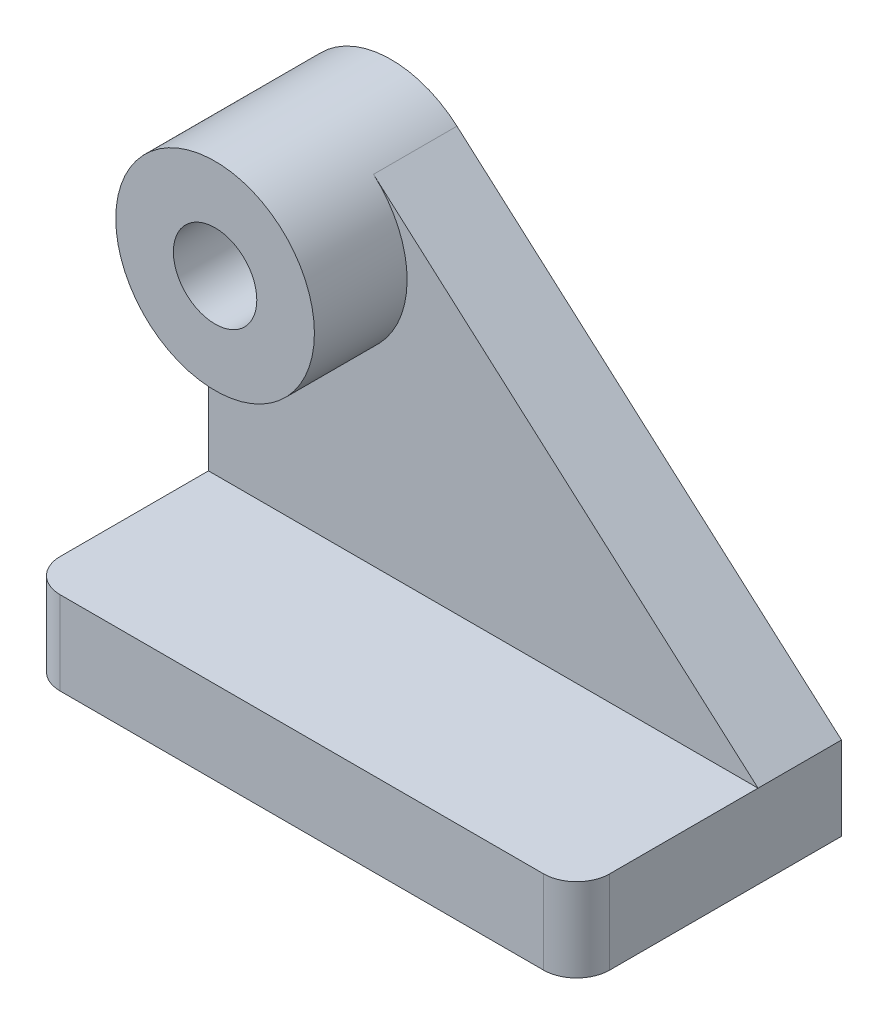
SolidWorks part; units mm, degrees
ref_plane "Alzado" through (0, 0, 0) normal (0, 0, 1) x (1, 0, 0)
ref_plane "Planta" through (0, 0, 0) normal (0, 1, 0) x (1, 0, 0)
ref_plane "Vista lateral" through (0, 0, 0) normal (1, 0, 0) x (0, 0, -1)
sketch "Croquis1" plane through (0, 0, 0) normal (0, 1, 0) x (1, 0, 0)
  line L1 (-2.0108, 1.1227) -> (2.1392, 1.1227)
  line L2 (-2.0108, 1.1227) -> (-2.0108, -0.6273)
  line L3 (-1.7608, -0.8773) -> (1.8892, -0.8773)
  line L4 (2.1392, 1.1227) -> (2.1392, -0.6273)
  arc A0 (1.8892, -0.8773) -> (2.1392, -0.6273) centre (1.8892, -0.6273) ccw
  arc A1 (-1.7608, -0.8773) -> (-2.0108, -0.6273) centre (-1.7608, -0.6273) cw
  point P6 (2.1392, -0.8773)
  dimension "D3" = 0.25
  dimension "D1" = 4.15
  dimension "D2" = 2
extrude "Saliente-Extruir1" add sketch "Croquis1" along normal blind 0.63
sketch "Croquis2" plane through (0, 0, -1.1227) normal (0, 0, -1) x (-1, 0, 0)
  line L0 (-2.1392, 0.63) -> (0.7645, 3.1924)
  line L1 (2.0108, 2.63) -> (2.0108, 0.63)
  line L2 (-2.1392, 0.63) -> (2.0108, 0.63)
  circle A0 centre (1.2608, 2.63) radius 0.315
  arc A1 (0.7645, 3.1924) -> (2.0108, 2.63) centre (1.2608, 2.63) cw
  point P1 (2.0108, 1.9061)
  point P10 (0, 0)
  dimension "D1" = 2
  dimension "D2" = 0.75
  dimension "D3" = 0.63
extrude "Saliente-Extruir2" add sketch "Croquis2" against normal blind 0.63
sketch "Croquis3" plane through (0, 0, -0.4927) normal (0, 0, 1) x (1, 0, 0)
  line L3 (-2.0108, 0.63) -> (2.1392, 0.63)
  line L4 (2.1392, 0.63) -> (-0.7645, 3.1924)
  line L5 (-2.0108, 2.63) -> (-2.0108, 0.63)
  line L6 (-2.0108, 0.63) -> (2.1392, 0.63)
  line L7 (2.1392, 0.63) -> (-0.7645, 3.1924)
  line L8 (-2.0108, 2.63) -> (-2.0108, 0.63)
  circle A0 centre (-1.2608, 2.63) radius 0.75
  arc A1 (-0.7645, 3.1924) -> (-2.0108, 2.63) centre (-1.2608, 2.63) ccw
  arc A2 (-0.7645, 3.1924) -> (-2.0108, 2.63) centre (-1.2608, 2.63) ccw
  circle A3 centre (-1.2608, 2.63) radius 0.315
  circle M1 centre (-1.2608, 2.63) radius 0.315
  arc M4 (-0.7645, 3.1924) -> (-2.0108, 2.63) centre (-1.2608, 2.63) ccw
  dimension "D1" = 0
extrude "Saliente-Extruir3" add sketch "Croquis3" along normal blind 0.7 contours A0 M4 M1
